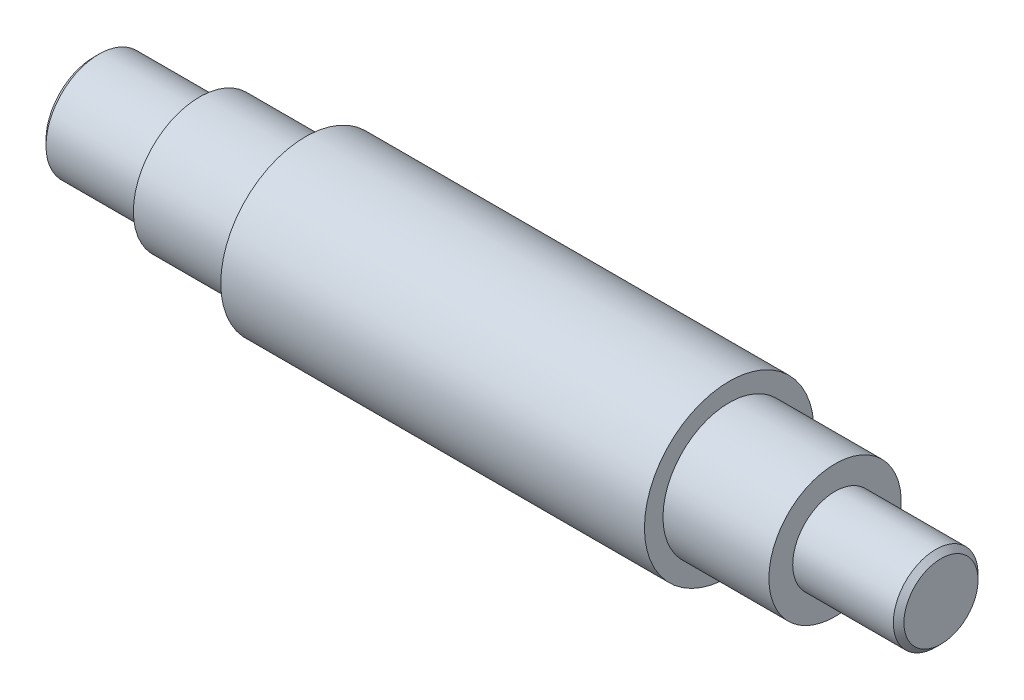
SolidWorks part; units mm, degrees
ref_plane "Ebene vorne" through (0, 0, 0) normal (0, 0, 1) x (1, 0, 0)
ref_plane "Ebene oben" through (0, 0, 0) normal (0, 1, 0) x (1, 0, 0)
ref_plane "Ebene rechts" through (0, 0, 0) normal (1, 0, 0) x (0, 0, -1)
sketch "Skizze1" plane through (0, 0, 0) normal (0, 0, 1) x (1, 0, 0)
  line L0 (0, 0) -> (0, 9)
  line L1 (0, 9) -> (1, 10)
  line L2 (1, 10) -> (20, 10)
  line L3 (20, 10) -> (20, 12.5)
  line L4 (20, 12.5) -> (40, 12.5)
  line L5 (40, 12.5) -> (40, 16)
  line L6 (40, 16) -> (120, 16)
  line L7 (120, 16) -> (120, 12.5)
  line L8 (120, 12.5) -> (140, 12.5)
  line L9 (140, 12.5) -> (140, 8)
  line L10 (140, 8) -> (159, 8)
  line L11 (159, 8) -> (160, 7)
  line L12 (160, 7) -> (160, 0)
  line L13 (160, 0) -> (0, 0)
  line L14 (-5, 0) -> (165, 0) construction
revolve "Welle" add sketch "Skizze1" angle 360 about L14
